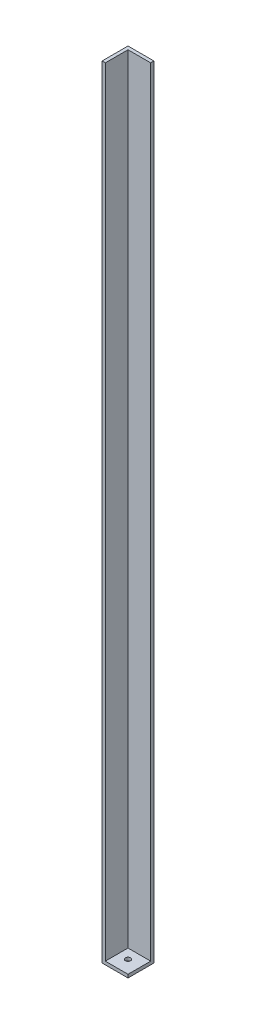
SolidWorks part; units mm, degrees
ref_plane "前视基准面" through (0, 0, 0) normal (0, 0, 1) x (1, 0, 0)
ref_plane "上视基准面" through (0, 0, 0) normal (0, 1, 0) x (1, 0, 0)
ref_plane "右视基准面" through (0, 0, 0) normal (1, 0, 0) x (0, 0, -1)
sketch "草图1" plane through (0, 0, 0) normal (0, 1, 0) x (1, 0, 0)
  line L0 (0, 44.2289) -> (0, -40.8267) construction
  line L1 (-20, 20) -> (20, 20)
  line L2 (-55.995, 0) -> (50.6081, 0) construction
  line L3 (20, 20) -> (20, -20)
  line L4 (20, -20) -> (-20, -20)
  line L5 (-20, -20) -> (-20, 20)
extrude "凸台-拉伸1" add sketch "草图1" along normal blind 5
sketch "草图2" plane through (0, 5, 0) normal (0, 1, 0) x (1, 0, 0)
  circle A0 centre (0, 0) radius 4.05
extrude "切除-拉伸1" cut sketch "草图2" against normal blind 5
sketch "草图3" plane through (0, 5, 0) normal (0, 1, 0) x (1, 0, 0)
  line L0 (-20, 20) -> (-20, -20)
  line L1 (-20, -20) -> (-15, -20)
  line L2 (-20, -20) -> (20, -20) construction
  line L3 (-15, -20) -> (-15, 15)
  line L4 (-15, 15) -> (20, 15)
  line L5 (20, -20) -> (20, 20) construction
  line L6 (20, 15) -> (20, 20)
  line L7 (20, 20) -> (-20, 20)
extrude "凸台-拉伸2" add sketch "草图3" along normal blind 600
mirror "镜向1" about plane through (0, 605, 0) normal (0, 1, 0) of "凸台-拉伸2", "切除-拉伸1", "凸台-拉伸1"
